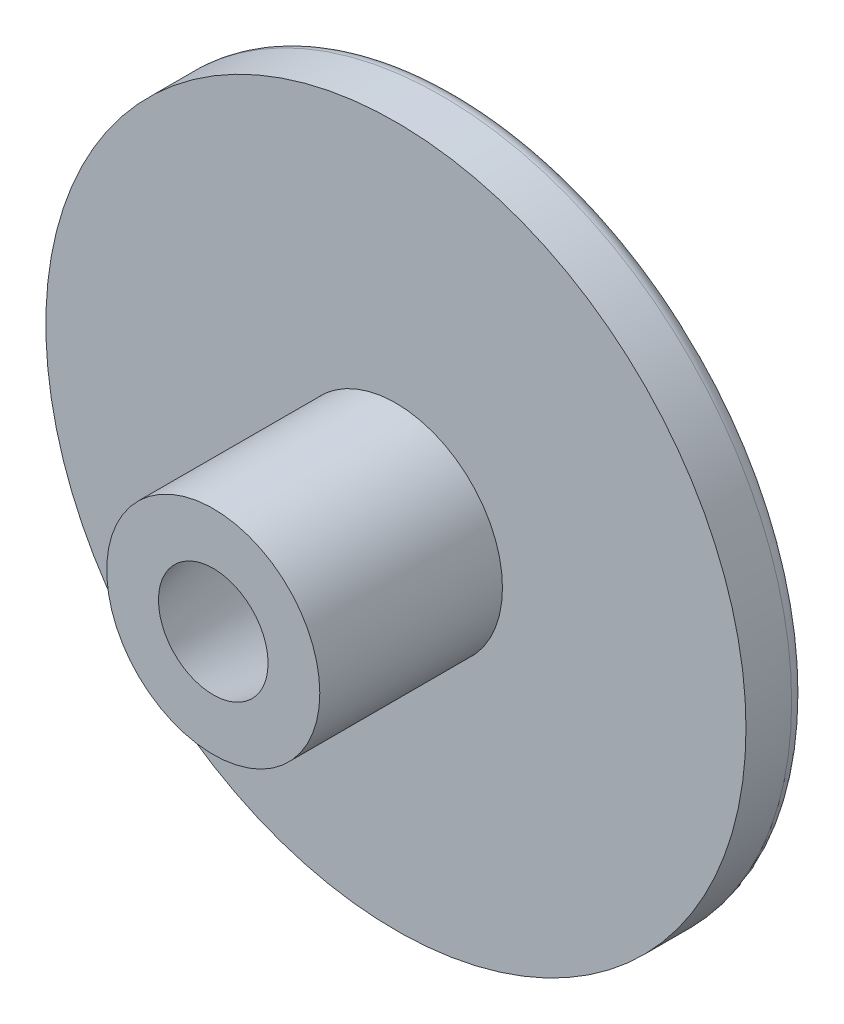
SolidWorks part; units mm, degrees
ref_plane "Plan de face" through (0, 0, 0) normal (0, 0, 1) x (1, 0, 0)
ref_plane "Plan de dessus" through (0, 0, 0) normal (0, 1, 0) x (1, 0, 0)
ref_plane "Plan de droite" through (0, 0, 0) normal (1, 0, 0) x (0, 0, -1)
sketch "Esquisse1" plane through (0, 0, 0) normal (0, 0, 1) x (1, 0, 0)
  circle A0 centre (0, 0) radius 3.5
  dimension "D1" = 7
extrude "Extru.-Mince1" add sketch "Esquisse1" along normal blind 2 thin
sketch "Esquisse2" plane through (0, 0, 2) normal (0, 0, 1) x (1, 0, 0)
  circle A0 centre (0, 0) radius 3.5
  dimension "D1" = 7
extrude "Boss.-Extru.1" add sketch "Esquisse2" along normal blind 6 and the other way blind 2 separate body
sketch "Esquisse3" plane through (0, 0, 0) normal (0, 0, -1) x (-1, 0, 0)
  circle A0 centre (0, 0) radius 3.5
extrude "Enlèv. mat.-Extru.1" cut sketch "Esquisse3" against normal blind 8 draft 12
sketch "Esquisse4" plane through (0, 0, 0) normal (0, 0, -1) x (-1, 0, 0)
  text T0 "ENTRER" font "Century Gothic" height 3.5
extrude "Enlèv. mat.-Extru.3" cut sketch "Esquisse4" against normal blind 0.5
fillet "Congé1" radius 0.5 1 edges at (11.5, 0, 0)
